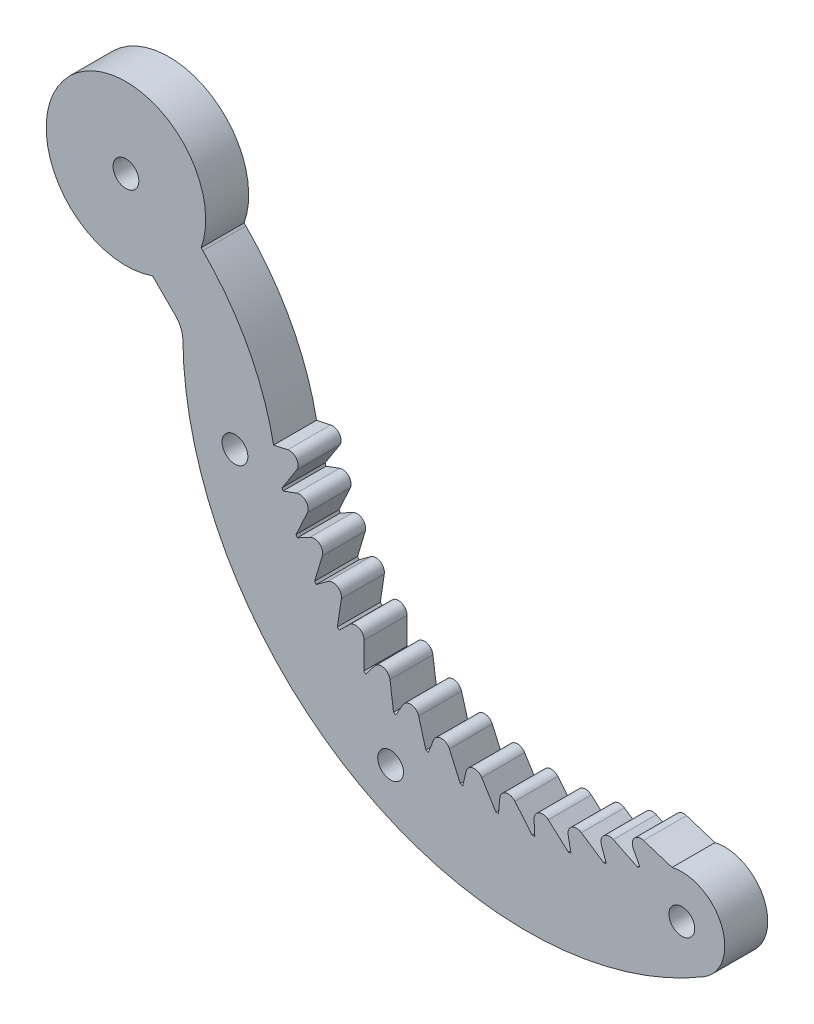
SolidWorks part; units mm, degrees
ref_plane "Plan de face" through (0, 0, 0) normal (0, 0, 1) x (1, 0, 0)
ref_plane "Plan de dessus" through (0, 0, 0) normal (0, 1, 0) x (1, 0, 0)
ref_plane "Plan de droite" through (0, 0, 0) normal (1, 0, 0) x (0, 0, -1)
sketch "Esquisse1" plane through (0, 0, 0) normal (0, 0, 1) x (1, 0, 0)
  line L0 (-26.279, 12.431) -> (-23.6257, 9.7778)
  line L1 (-20.6221, 18.0878) -> (-20.4272, 17.8929)
  arc A0 (37.8784, -26.1046) -> (32.7212, -17.5369) centre (35.2998, -21.8207) ccw
  arc A1 (-12.1952, 2.4228) -> (32.7212, -17.5369) centre (17.2499, 8.166) ccw
  arc A3 (-22.7473, 7.692) -> (37.8784, -26.1046) centre (17.2499, 8.166) ccw
  arc A4 (-22.7473, 7.692) -> (-23.6257, 9.7778) centre (-25.7471, 7.6564) ccw
  arc A5 (-12.1952, 2.4228) -> (-20.4272, 17.8929) centre (-41.6404, -3.3203) ccw
  arc A6 (-20.6221, 18.0878) -> (-26.279, 12.431) centre (-29.3718, 21.1807) ccw
  circle A7 centre (-29.3718, 21.1807) radius 3.5
extrude "Boss.-Extru.1" add sketch "Esquisse1" along normal blind 5
sketch "Esquisse2" plane through (0, 0, 5) normal (0, 0, 1) x (1, 0, 0)
  circle A0 centre (-29.3718, 21.1807) radius 1.5
  circle A1 centre (-29.3718, 21.1807) radius 3.5 construction
  circle A2 centre (-29.3718, 21.1807) radius 3.5
  dimension "D1" = 3
extrude "Boss.-Extru.2" add sketch "Esquisse2" against normal through all
sketch "Esquisse3" plane through (0, 0, 5) normal (0, 0, 1) x (1, 0, 0)
  circle A0 centre (35.2998, -21.8207) radius 1.5
  circle A1 centre (1.4203, -23.0106) radius 1.5
  circle A2 centre (-16.6903, -0.2447) radius 1.5
extrude "Enlèv. mat.-Extru.1" cut sketch "Esquisse3" against normal through all
sketch "Esquisse4" plane through (0, 0, 0) normal (0, 0, -1) x (-1, 0, 0)
  line L0 (11.0962, -1.6573) -> (9.522, -1.0759) construction
  line L1 (8.2673, -2.4323) -> (9.5737, -5.2689) construction
  line L2 (-30.4183, -18.7894) -> (-29.6514, -17.2968) construction
  line L3 (-30.8467, -15.8877) -> (-33.82, -16.8427) construction
  line L4 (-33.82, -16.8427) -> (-34.1609, -16.9522) construction
  line L5 (12.1952, 2.4228) -> (10.555, 2.7773) construction
  line L6 (9.5032, 1.258) -> (11.1952, -1.3668) construction
  line L7 (1.4577, -15.2866) -> (0.438, -13.9539) construction
  line L8 (-1.3475, -14.4297) -> (-1.7593, -17.5253) construction
  line L9 (4.5673, -12.4255) -> (3.3704, -11.2493) construction
  line L10 (1.6695, -11.9712) -> (1.6967, -15.094) construction
  line L11 (7.244, -9.1559) -> (5.8938, -8.1595) construction
  line L12 (4.3112, -9.1132) -> (4.7768, -12.2012) construction
  line L13 (9.4348, -5.5426) -> (7.958, -4.7458) construction
  line L14 (6.5251, -5.9124) -> (7.42, -8.9044) construction
  line L15 (-9.8156, -20.8983) -> (-10.1986, -19.2645) construction
  line L16 (-12.022, -18.9656) -> (-13.6681, -21.6195) construction
  line L17 (-5.8058, -19.5655) -> (-6.4145, -18.0016) construction
  line L18 (-8.2618, -17.9619) -> (-9.5187, -20.8207) construction
  line L19 (-2.023, -17.6825) -> (-2.8454, -16.2197) construction
  line L20 (-4.6799, -16.4399) -> (-5.5227, -19.4469) construction
  line L21 (-22.399, -21.3889) -> (-22.0776, -19.7418) construction
  line L22 (-23.6177, -18.7209) -> (-26.208, -20.4654) construction
  line L23 (-18.1954, -21.8191) -> (-18.1086, -20.1433) construction
  line L24 (-19.7769, -19.3489) -> (-22.0963, -21.44) construction
  line L25 (-13.973, -21.6545) -> (-14.1226, -19.9831) construction
  line L26 (-15.8859, -19.431) -> (-17.8885, -21.8272) construction
  line L27 (-26.5004, -20.3722) -> (-25.9508, -18.7867) construction
  line L28 (-27.3322, -17.5595) -> (-30.1419, -18.9227) construction
  line L29 (11.0962, -1.6573) -> (9.522, -1.0759)
  line L30 (8.2673, -2.4323) -> (9.5737, -5.2689)
  line L31 (-30.4183, -18.7894) -> (-29.6514, -17.2968)
  line L32 (-30.8467, -15.8877) -> (-33.82, -16.8427)
  line L33 (-33.82, -16.8427) -> (-34.1609, -16.9522)
  line L34 (12.1952, 2.4228) -> (10.555, 2.7773)
  line L35 (9.5032, 1.258) -> (11.1952, -1.3668)
  line L36 (1.4577, -15.2866) -> (0.438, -13.9539)
  line L37 (-1.3475, -14.4297) -> (-1.7593, -17.5253)
  line L38 (4.5673, -12.4255) -> (3.3704, -11.2493)
  line L39 (1.6695, -11.9712) -> (1.6967, -15.094)
  line L40 (7.244, -9.1559) -> (5.8938, -8.1595)
  line L41 (4.3112, -9.1132) -> (4.7768, -12.2012)
  line L42 (9.4348, -5.5426) -> (7.958, -4.7458)
  line L43 (6.5251, -5.9124) -> (7.42, -8.9044)
  line L44 (-9.8156, -20.8983) -> (-10.1986, -19.2645)
  line L45 (-12.022, -18.9656) -> (-13.6681, -21.6195)
  line L46 (-5.8058, -19.5655) -> (-6.4145, -18.0016)
  line L47 (-8.2618, -17.9619) -> (-9.5187, -20.8207)
  line L48 (-2.023, -17.6825) -> (-2.8454, -16.2197)
  line L49 (-4.6799, -16.4399) -> (-5.5227, -19.4469)
  line L50 (-22.399, -21.3889) -> (-22.0776, -19.7418)
  line L51 (-23.6177, -18.7209) -> (-26.208, -20.4654)
  line L52 (-18.1954, -21.8191) -> (-18.1086, -20.1433)
  line L53 (-19.7769, -19.3489) -> (-22.0963, -21.44)
  line L54 (-13.973, -21.6545) -> (-14.1226, -19.9831)
  line L55 (-15.8859, -19.431) -> (-17.8885, -21.8272)
  line L56 (-26.5004, -20.3722) -> (-25.9508, -18.7867)
  line L57 (-27.3322, -17.5595) -> (-30.1419, -18.9227)
  arc A0 (9.522, -1.0759) -> (8.2673, -2.4323) centre (9.1756, -2.014) ccw construction
  arc A1 (-29.6514, -17.2968) -> (-30.8467, -15.8877) centre (-30.5409, -16.8398) ccw construction
  arc A2 (-32.7212, -17.5369) -> (-34.1609, -16.9522) centre (-35.2998, -21.8207) ccw construction
  arc A3 (-32.7212, -17.5369) -> (12.1952, 2.4228) centre (-17.2499, 8.166) ccw construction
  arc A4 (10.555, 2.7773) -> (9.5032, 1.258) centre (10.3437, 1.7998) ccw construction
  arc A5 (0.438, -13.9539) -> (-1.3475, -14.4297) centre (-0.3562, -14.5615) ccw construction
  arc A6 (3.3704, -11.2493) -> (1.6695, -11.9712) centre (2.6695, -11.9625) ccw construction
  arc A7 (5.8938, -8.1595) -> (4.3112, -9.1132) centre (5.3, -8.9641) ccw construction
  arc A8 (7.958, -4.7458) -> (6.5251, -5.9124) centre (7.4831, -5.6259) ccw construction
  arc A9 (-10.1986, -19.2645) -> (-12.022, -18.9656) centre (-11.1722, -19.4927) ccw construction
  arc A10 (-6.4145, -18.0016) -> (-8.2618, -17.9619) centre (-7.3464, -18.3644) ccw construction
  arc A11 (-2.8454, -16.2197) -> (-4.6799, -16.4399) centre (-3.717, -16.7097) ccw construction
  arc A12 (-22.0776, -19.7418) -> (-23.6177, -18.7209) centre (-23.0591, -19.5503) ccw construction
  arc A13 (-18.1086, -20.1433) -> (-19.7769, -19.3489) centre (-19.1073, -20.0916) ccw construction
  arc A14 (-14.1226, -19.9831) -> (-15.8859, -19.431) centre (-15.1186, -20.0722) ccw construction
  arc A15 (-25.9508, -18.7867) -> (-27.3322, -17.5595) centre (-26.8957, -18.4592) ccw construction
  arc A16 (9.522, -1.0759) -> (8.2673, -2.4323) centre (9.1756, -2.014) ccw
  arc A17 (-29.6514, -17.2968) -> (-30.8467, -15.8877) centre (-30.5409, -16.8398) ccw
  arc A18 (-32.7212, -17.5369) -> (-34.1609, -16.9522) centre (-35.2998, -21.8207) ccw
  arc A19 (-32.7212, -17.5369) -> (12.1952, 2.4228) centre (-17.2499, 8.166) ccw
  arc A20 (10.555, 2.7773) -> (9.5032, 1.258) centre (10.3437, 1.7998) ccw
  arc A21 (0.438, -13.9539) -> (-1.3475, -14.4297) centre (-0.3562, -14.5615) ccw
  arc A22 (3.3704, -11.2493) -> (1.6695, -11.9712) centre (2.6695, -11.9625) ccw
  arc A23 (5.8938, -8.1595) -> (4.3112, -9.1132) centre (5.3, -8.9641) ccw
  arc A24 (7.958, -4.7458) -> (6.5251, -5.9124) centre (7.4831, -5.6259) ccw
  arc A25 (-10.1986, -19.2645) -> (-12.022, -18.9656) centre (-11.1722, -19.4927) ccw
  arc A26 (-6.4145, -18.0016) -> (-8.2618, -17.9619) centre (-7.3464, -18.3644) ccw
  arc A27 (-2.8454, -16.2197) -> (-4.6799, -16.4399) centre (-3.717, -16.7097) ccw
  arc A28 (-22.0776, -19.7418) -> (-23.6177, -18.7209) centre (-23.0591, -19.5503) ccw
  arc A29 (-18.1086, -20.1433) -> (-19.7769, -19.3489) centre (-19.1073, -20.0916) ccw
  arc A30 (-14.1226, -19.9831) -> (-15.8859, -19.431) centre (-15.1186, -20.0722) ccw
  arc A31 (-25.9508, -18.7867) -> (-27.3322, -17.5595) centre (-26.8957, -18.4592) ccw
  arc M10 (12.1952, 2.4228) -> (-32.7212, -17.5369) centre (-17.2499, 8.166) cw
  arc M11 (-32.7212, -17.5369) -> (-37.8784, -26.1046) centre (-35.2998, -21.8207) ccw
extrude "Boss.-Extru.3" add sketch "Esquisse4" against normal through all contours L31 A17 L32 L33 M11 M10 | L56 A31 L57 M10 | L50 A28 L51 M10 | L52 A29 L53 M10 | L54 A30 L55 M10 | L44 A25 L45 M10 | L46 A26 L47 M10 | L48 A27 L49 M10 | L36 A21 L37 M10 | L34 A20 L35 M10 | L29 A16 L30 M10 | L42 A24 L43 M10 | L40 A23 L41 M10 | L38 A22 L39 M10
